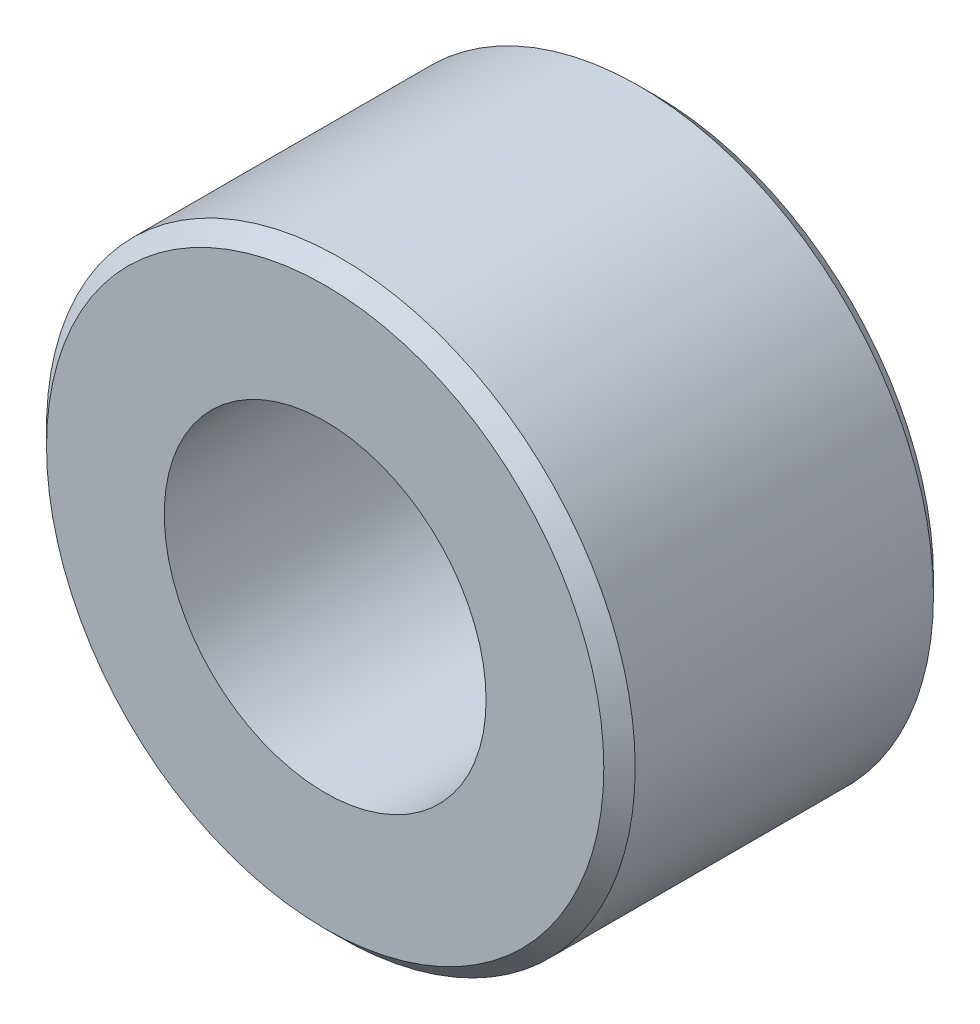
SolidWorks part; units mm, degrees
ref_plane "Front Plane" through (0, 0, 0) normal (0, 0, 1) x (1, 0, 0)
ref_plane "Top Plane" through (0, 0, 0) normal (0, 1, 0) x (1, 0, 0)
ref_plane "Right Plane" through (0, 0, 0) normal (1, 0, 0) x (0, 0, -1)
sketch "Sketch1" plane through (0, 0, 0) normal (0, 0, 1) x (1, 0, 0)
  circle A0 centre (0, 0) radius 4.1
  circle A1 centre (0, 0) radius 7.5
  dimension "D1" = 8.2
  dimension "D2" = 15
extrude "Boss-Extrude1" add sketch "Sketch1" along normal mid plane 8.4
chamfer "Chamfer1" distance 0.4 angle 45 2 edges at (7.5, 0, -4.2) (7.5, 0, 4.2)
